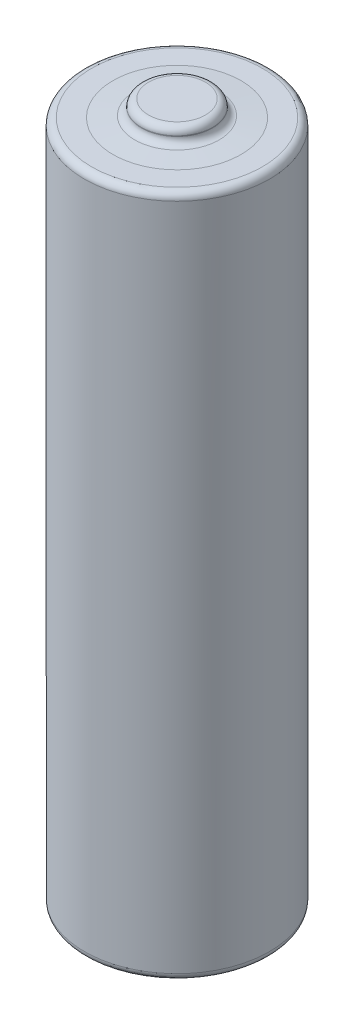
SolidWorks part; units mm, degrees
ref_plane "Alzado" through (0, 0, 0) normal (0, 0, 1) x (1, 0, 0)
ref_plane "Planta" through (0, 0, 0) normal (0, 1, 0) x (1, 0, 0)
ref_plane "Vista lateral" through (0, 0, 0) normal (1, 0, 0) x (0, 0, -1)
sketch "Croquis2" plane through (0, 0, 0) normal (1, 0, 0) x (0, 0, -1)
  line L0 (2.0837, 15.9161) -> (4.5837, 15.9161)
  line L1 (4.5837, 15.9161) -> (4.5837, 14.9161)
  line L3 (4.5837, 14.9161) -> (6.5837, 14.7635)
  line L4 (6.5837, 14.7635) -> (8.5837, 14.7635)
  line L5 (8.5837, 14.7635) -> (8.5837, -33.2365)
  line L6 (8.5837, -33.2365) -> (6.0837, -33.2365)
  line L7 (6.0837, -33.2365) -> (6.0837, -34.2365)
  line L8 (6.0837, -34.2365) -> (2.0837, -34.2365)
  line L9 (2.0837, -34.2365) -> (2.0837, 15.9161)
  dimension "D1" = 48
  dimension "D2" = 1
  dimension "D3" = 1
  dimension "D4" = 2
  dimension "D5" = 6.5
  dimension "D6" = 2.5
  dimension "D7" = 4
revolve "Revolución1" add sketch "Croquis2" angle 360 about L9
fillet "Redondeo1" radius 0.5 5 edges at (0, 15.9161, -4.5837) (0, -33.2365, -8.5837) (0, 14.7635, -8.5837) (0, 14.9161, -4.5837) (0, -34.2365, -6.0837)
